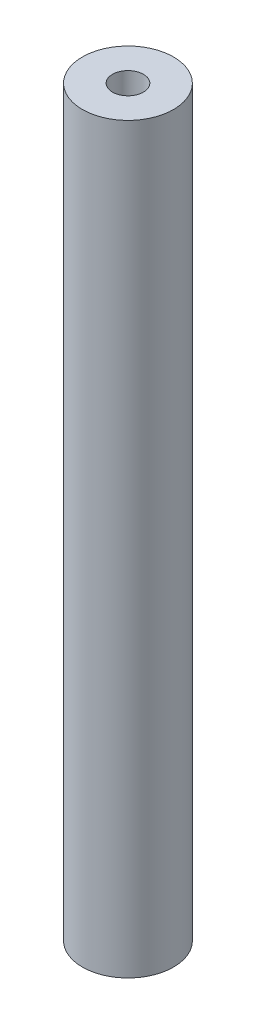
SolidWorks part; units mm, degrees
material "Rubber"
ref_plane "Front Plane" through (0, 0, 0) normal (0, 0, 1) x (1, 0, 0)
ref_plane "Top Plane" through (0, 0, 0) normal (0, 1, 0) x (1, 0, 0)
ref_plane "Right Plane" through (0, 0, 0) normal (1, 0, 0) x (0, 0, -1)
sketch "Sketch1" plane through (0, 0, 0) normal (0, 1, 0) x (1, 0, 0)
  circle A1 centre (0, 0) radius 14.725
  circle A2 centre (0, 0) radius 5
  dimension "D1" = 10
  dimension "D2" = 29.45
extrude "Boss-Extrude1" add sketch "Sketch1" along normal blind 240
